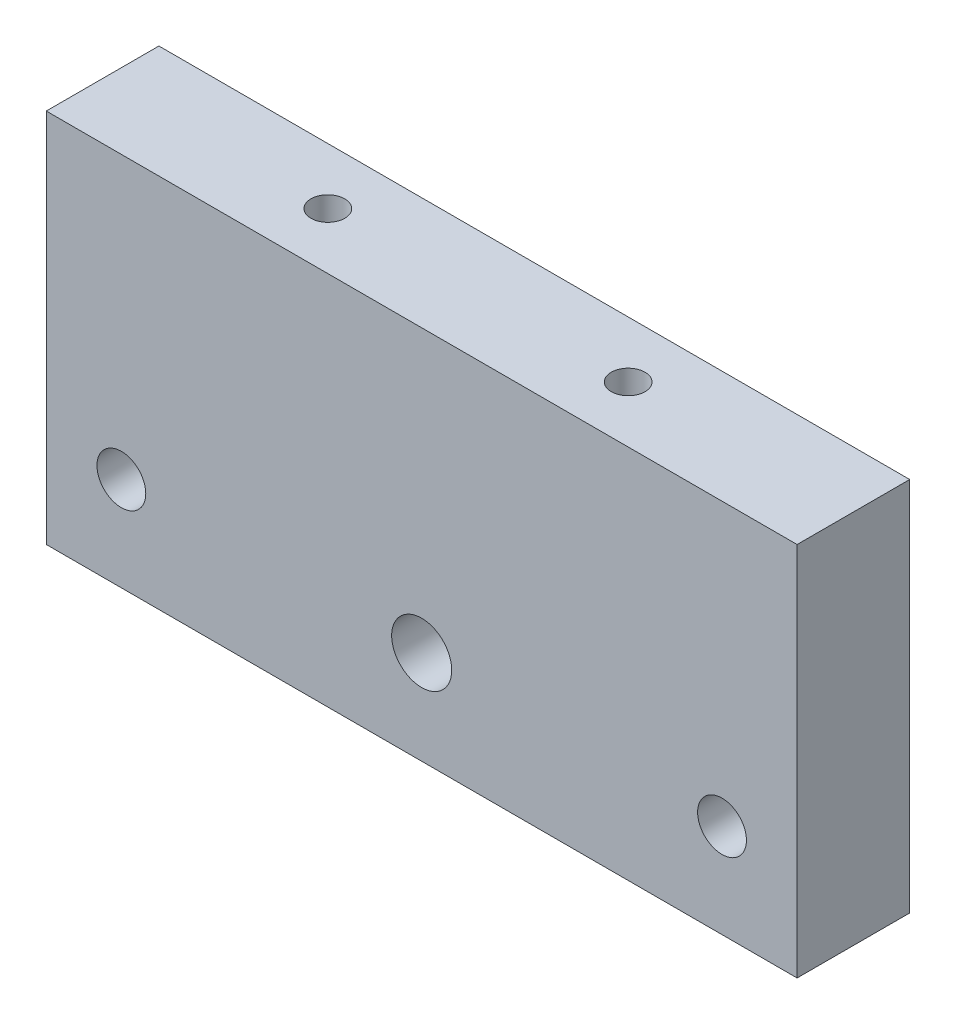
SolidWorks part; units mm, degrees
ref_plane "前视基准面" through (0, 0, 0) normal (0, 0, 1) x (1, 0, 0)
ref_plane "上视基准面" through (0, 0, 0) normal (0, 1, 0) x (1, 0, 0)
ref_plane "右视基准面" through (0, 0, 0) normal (1, 0, 0) x (0, 0, -1)
sketch "草图1" plane through (0, 0, 0) normal (0, 0, 1) x (1, 0, 0)
  line L1 (0, 0) -> (200, 0)
  line L2 (0, 0) -> (0, 100)
  line L3 (0, 100) -> (200, 100)
  line L4 (200, 0) -> (200, 100)
  dimension "D1" = 200
  dimension "D2" = 100
extrude "凸台-拉伸1" add sketch "草图1" along normal blind 30
sketch "草图2" plane through (0, 0, 30) normal (0, 0, 1) x (1, 0, 0)
  line L0 (200, 0) -> (200, 100) construction
  line L1 (0, 0) -> (200, 0) construction
  circle A0 centre (20, 25) radius 4.5
  circle A1 centre (100, 25) radius 8
  circle A2 centre (180, 25) radius 4.5
  dimension "D1" = 9
  dimension "D2" = 9
  dimension "D3" = 16
  dimension "D4" = 80
  dimension "D5" = 80
  dimension "D6" = 20
  dimension "D7" = 25
  dimension "D8" = 25
  dimension "D9" = 25
extrude "切除-拉伸1" cut sketch "草图2" against normal through all
sketch "草图3" plane through (0, 0, 0) normal (0, -1, 0) x (1, 0, 0)
  line L0 (200, 30) -> (200, 0) construction
  line L1 (0, 30) -> (0, 0) construction
  circle A0 centre (60, 15) radius 4.5
  circle A1 centre (140, 15) radius 4.5
  dimension "D1" = 9
  dimension "D2" = 9
  dimension "D3" = 60
  dimension "D4" = 60
extrude "切除-拉伸2" cut sketch "草图3" against normal through all
sketch "草图4" plane through (0, 0, 0) normal (0, -1, 0) x (1, 0, 0)
  circle A0 centre (60, 15) radius 6.5
  circle A1 centre (140, 15) radius 6.5
  dimension "D1" = 13
  dimension "D2" = 13
extrude "切除-拉伸3" cut sketch "草图4" against normal blind 50
sketch "草图5" plane through (0, 0, 30) normal (0, 0, 1) x (1, 0, 0)
  circle A0 centre (20, 25) radius 6.5
  circle A1 centre (180, 25) radius 6.5
  dimension "D1" = 13
  dimension "D2" = 13
extrude "切除-拉伸4" cut sketch "草图5" against normal blind 15
sketch "草图6" plane through (0, 0, 0) normal (0, 0, -1) x (-1, 0, 0)
  circle A0 centre (-100, 25) radius 12
  dimension "D1" = 24
extrude "切除-拉伸5" cut sketch "草图6" against normal blind 15
